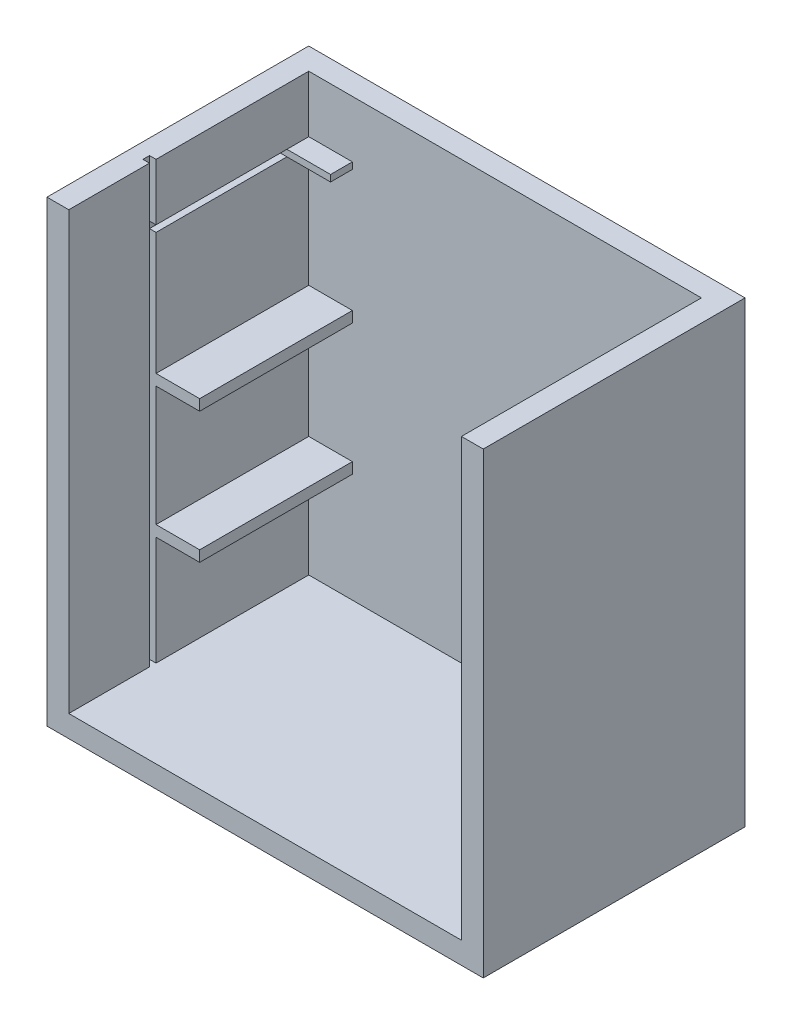
SolidWorks part; units mm, degrees
ref_plane "Front Plane" through (0, 0, 0) normal (0, 0, 1) x (1, 0, 0)
ref_plane "Top Plane" through (0, 0, 0) normal (0, 1, 0) x (1, 0, 0)
ref_plane "Right Plane" through (0, 0, 0) normal (1, 0, 0) x (0, 0, -1)
sketch "Sketch1" plane through (0, 0, 0) normal (0, 1, 0) x (1, 0, 0)
  line L0 (0, 0) -> (200, 0)
  line L1 (200, 0) -> (200, 120)
  line L2 (200, 120) -> (0, 120)
  line L3 (0, 120) -> (0, 0)
  dimension "D1" = 200
  dimension "D2" = 120
extrude "Boss-Extrude2" add sketch "Sketch1" along normal blind 10
sketch "Sketch2" plane through (0, 10, 0) normal (0, 1, 0) x (1, 0, 0)
  line L0 (0, 120) -> (200, 120)
  line L1 (200, 120) -> (200, 110)
  line L2 (200, 0) -> (200, 120) construction
  line L3 (200, 110) -> (0, 110)
  line L4 (0, 120) -> (0, 0) construction
  line L5 (0, 110) -> (0, 120)
  line L6 (0, 110) -> (0, 0)
  line L7 (0, 0) -> (10, 0)
  line L8 (0, 0) -> (200, 0) construction
  line L9 (10, 0) -> (10, 110)
  line L10 (200, 110) -> (200, 0)
  line L11 (200, 0) -> (190, 0)
  line L12 (190, 0) -> (190, 110)
  line M4 (0, 120) -> (0, 0)
  line M5 (0, 0) -> (200, 0)
  line M6 (200, 0) -> (200, 120)
  line M7 (200, 120) -> (0, 120)
  dimension "D1" = 10
  dimension "D2" = 10
  dimension "D3" = 10
  dimension "D4" = 110
extrude "Boss-Extrude3" add sketch "Sketch2" along normal blind 200 contours L9 L3 M5 M4 | L3 M6 M7 M4 | L12 L3 M5 M6
sketch "Sketch3" plane through (10, 0, 0) normal (1, 0, 0) x (0, 0, -1)
  line L0 (120, 0) -> (120, 60)
  line L1 (120, 210) -> (120, 0) construction
  line L2 (120, 60) -> (120, 120)
  line L3 (120, 120) -> (120, 180)
  line L4 (120, 60) -> (40, 60)
  line L5 (40, 60) -> (40, 65)
  line L6 (40, 65) -> (120, 65)
  line L7 (120, 120) -> (40, 120)
  line L8 (40, 120) -> (40, 125)
  line L9 (40, 125) -> (120, 125)
  line L10 (120, 180) -> (40, 180)
  line L11 (40, 180) -> (40, 185)
  line L12 (40, 185) -> (120, 185)
  line M11 (110, 10) -> (110, 210)
  dimension "D1" = 60
  dimension "D2" = 60
  dimension "D3" = 60
  dimension "D4" = 80
  dimension "D5" = 5
  dimension "D6" = 80
  dimension "D7" = 5
  dimension "D8" = 80
  dimension "D9" = 5
extrude "Boss-Extrude4" add sketch "Sketch3" along normal blind 20 contours L12 L11 L10 M11 | L9 L8 L7 M11 | L6 L5 L4 M11
sketch "Sketch4" plane through (190, 0, 0) normal (-1, 0, 0) x (0, 0, 1)
  line L0 (-120, 0) -> (-120, 60)
  line L1 (-120, 210) -> (-120, 0) construction
  line L2 (-120, 60) -> (-120, 120)
  line L3 (-120, 120) -> (-120, 180)
  line L4 (-120, 60) -> (-40, 60)
  line L5 (-40, 60) -> (-40, 65)
  line L6 (-40, 65) -> (-120, 65)
  line L7 (-120, 120) -> (-40, 120)
  line L8 (-40, 120) -> (-40, 125)
  line L9 (-40, 125) -> (-120, 125)
  line L10 (-120, 180) -> (-40, 180)
  line L11 (-40, 180) -> (-40, 185)
  line L12 (-40, 185) -> (-120, 185)
  line M13 (-110, 210) -> (-110, 10)
  dimension "D1" = 60
  dimension "D2" = 60
  dimension "D3" = 60
  dimension "D4" = 80
  dimension "D5" = 80
  dimension "D6" = 80
  dimension "D7" = 5
  dimension "D8" = 5
  dimension "D9" = 5
extrude "Boss-Extrude5" add sketch "Sketch4" along normal blind 20 contours L11 L12 L10 M13 | L8 L9 L7 M13 | L5 L6 L4 M13
sketch "Sketch6" plane through (0, 0, -40) normal (0, 0, 1) x (1, 0, 0)
  line L0 (30, 185) -> (30, 184)
  line L1 (30, 180) -> (30, 185) construction
  line L2 (30, 184) -> (10, 184)
  line L3 (10, 210) -> (10, 10) construction
  line L4 (10, 184) -> (10, 181)
  line L5 (10, 180) -> (10, 185) construction
  line L6 (10, 181) -> (30, 181)
  line L7 (30, 181) -> (30, 184)
  line M3 (10, 185) -> (10, 180)
  line M5 (30, 180) -> (30, 185)
  dimension "D1" = 3
  dimension "D2" = 1
extrude "Cut-Extrude1" cut sketch "Sketch6" against normal blind 80 contours L6 L2 M3 M5
sketch "Sketch7" plane through (10, 0, 0) normal (1, 0, 0) x (0, 0, -1)
  line L0 (40, 185) -> (40, 210)
  line L1 (0, 210) -> (110, 210) construction
  line L2 (40, 210) -> (37, 210)
  line L3 (37, 210) -> (37, 10)
  line L4 (0, 10) -> (110, 10) construction
  line L5 (37, 10) -> (40, 10)
  line L6 (40, 10) -> (40, 185)
  dimension "D1" = 3
extrude "Cut-Extrude2" cut sketch "Sketch7" against normal blind 3
sketch "Sketch9" plane through (10, 0, 0) normal (1, 0, 0) x (0, 0, -1)
  line L0 (40, 184) -> (40, 181)
  line L1 (40, 181) -> (120, 181)
  line L2 (120, 181) -> (120, 184)
  line L3 (120, 184) -> (40, 184)
  point P9 (40, 184)
extrude "Cut-Extrude5" cut sketch "Sketch9" against normal blind 3
sketch "Sketch10" plane through (0, 0, -40) normal (0, 0, 1) x (1, 0, 0)
  line L0 (10, 185) -> (10, 184)
  line L1 (10, 210) -> (10, 10) construction
  line L2 (30, 184) -> (7, 184) construction
  line L3 (10, 184) -> (30, 184)
  line L4 (30, 184) -> (30, 185)
  line L5 (30, 185) -> (10, 185)
  line L6 (10, 181) -> (10, 180)
  line L7 (7, 181) -> (30, 181) construction
  line L8 (10, 180) -> (30, 180)
  line L9 (30, 180) -> (10, 180) construction
  line L10 (30, 180) -> (10, 180) construction
  line L11 (30, 180) -> (30, 181)
  line L12 (30, 180) -> (30, 181) construction
  line L13 (30, 180) -> (30, 181) construction
  line L14 (30, 181) -> (10, 181)
extrude "Cut-Extrude6" cut sketch "Sketch10" against normal blind 70
sketch "Sketch11" plane through (0, 0, -120) normal (0, 0, -1) x (-1, 0, 0)
  line L0 (-7, 184) -> (-7, 181)
  line L1 (-7, 181) -> (-30, 181)
  line L2 (-30, 181) -> (-30, 184)
  line L3 (-30, 184) -> (-7, 184)
extrude "Boss-Extrude6" add sketch "Sketch11" against normal blind 20
